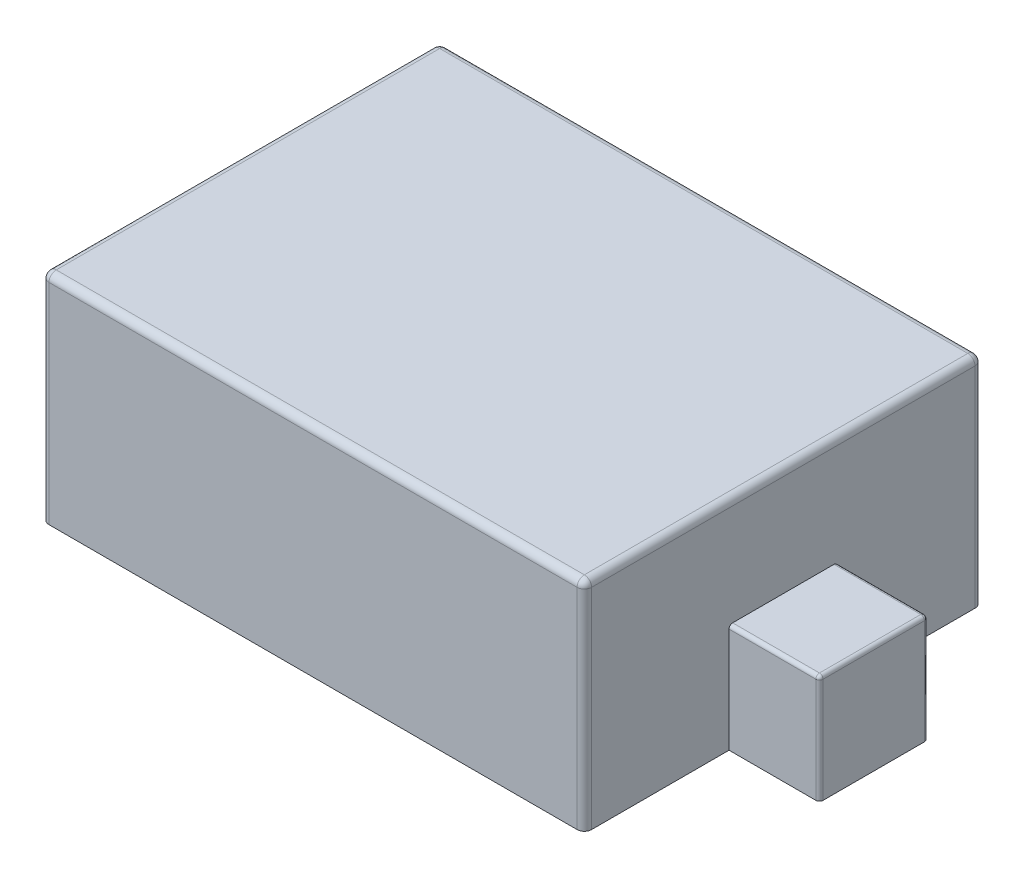
SolidWorks part; units mm, degrees
ref_plane "Front Plane" through (0, 0, 0) normal (0, 0, 1) x (1, 0, 0)
ref_plane "Top Plane" through (0, 0, 0) normal (0, 1, 0) x (1, 0, 0)
ref_plane "Right Plane" through (0, 0, 0) normal (1, 0, 0) x (0, 0, -1)
sketch "Sketch1" plane through (0, 0, 0) normal (0, 1, 0) x (1, 0, 0)
  line L1 (-0.73, -0.55) -> (0.73, -0.55)
  line L2 (-0.75, -0.53) -> (-0.75, 0.53)
  line L3 (-0.73, 0.55) -> (0.73, 0.55)
  line L4 (0.75, -0.53) -> (0.75, 0.53)
  line L5 (-0.75, -0.55) -> (0.75, 0.55) construction
  line L6 (-0.75, 0.55) -> (0.75, -0.55) construction
  arc A0 (-0.73, -0.55) -> (-0.75, -0.53) centre (-0.73, -0.53) cw
  arc A1 (0.73, -0.55) -> (0.75, -0.53) centre (0.73, -0.53) ccw
  arc A2 (0.73, 0.55) -> (0.75, 0.53) centre (0.73, 0.53) cw
  arc A3 (-0.75, 0.53) -> (-0.73, 0.55) centre (-0.73, 0.53) cw
  point P0 (0, 0)
  dimension "D3" = 0.02
  dimension "D1" = 1.5
  dimension "D2" = 1.1
extrude "Boss-Extrude1" add sketch "Sketch1" along normal mid plane 0.6
fillet "Fillet1" radius 0.02 8 edges at (-0.7441, 0.3, 0.5441) (-0.75, 0.3, 0) (-0.7441, 0.3, -0.5441) (0, 0.3, -0.55) (0.7441, 0.3, -0.5441) (0.7441, 0.3, 0.5441) (0.75, 0.3, 0) (0, 0.3, 0.55)
sketch "Sketch2" plane through (0, -0.3, 0) normal (0, -1, 0) x (1, 0, 0)
  line L0 (-0.75, 0.53) -> (-0.75, -0.53) construction
  line L1 (-0.75, -0.15) -> (-1, -0.15)
  line L2 (-0.75, -0.15) -> (-0.75, 0.15)
  line L3 (-0.75, 0.15) -> (-1, 0.15)
  line L4 (-1, -0.15) -> (-1, 0.15)
  line L5 (-0.75, -0.15) -> (-1, 0.15) construction
  line L6 (-0.75, 0.15) -> (-1, -0.15) construction
  line L7 (0, 0) -> (0, -0.5785) construction
  line L8 (0.75, 0.15) -> (1, -0.15) construction
  line L9 (0.75, -0.15) -> (1, 0.15) construction
  line L10 (1, -0.15) -> (1, 0.15)
  line L11 (0.75, 0.15) -> (1, 0.15)
  line L12 (0.75, -0.15) -> (0.75, 0.15)
  line L13 (0.75, -0.15) -> (1, -0.15)
  point P4 (-0.875, 0)
  point P14 (0.875, 0)
  dimension "D1" = 0.25
  dimension "D2" = 0.3
extrude "Boss-Extrude2" add sketch "Sketch2" against normal blind 0.3
fillet "Fillet2" radius 0.01 10 edges at (-1, -0.15, -0.15) (-0.875, 0, -0.15) (-1, 0, 0) (-0.875, 0, 0.15) (-1, -0.15, 0.15) (1, -0.15, -0.15) (1, -0.15, 0.15) (0.875, 0, -0.15) (1, 0, 0) (0.875, 0, 0.15)
